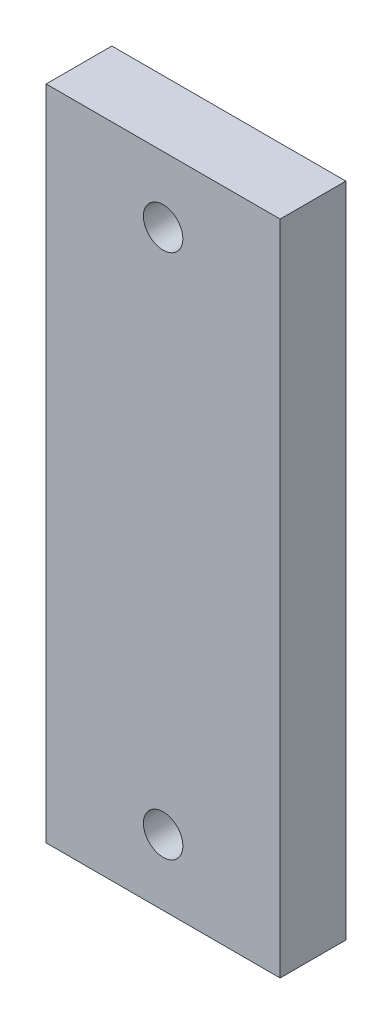
SolidWorks part; units mm, degrees
material "ABS"
ref_plane "前视基准面" through (0, 0, 0) normal (0, 0, 1) x (1, 0, 0)
ref_plane "上视基准面" through (0, 0, 0) normal (0, 1, 0) x (1, 0, 0)
ref_plane "右视基准面" through (0, 0, 0) normal (1, 0, 0) x (0, 0, -1)
sketch "草图1" plane through (0, 0, 0) normal (0, 0, 1) x (1, 0, 0)
  line L0 (0, -25) -> (0, 25) construction
  line L1 (-8.9, -25) -> (8.9, -25)
  line L2 (-8.9, -25) -> (-8.9, 25)
  line L3 (-8.9, 25) -> (8.9, 25)
  line L4 (8.9, -25) -> (8.9, 25)
  line L5 (-8.9, -25) -> (8.9, 25) construction
  line L6 (-8.9, 25) -> (8.9, -25) construction
  circle A0 centre (0, -20) radius 1.5
  circle A1 centre (0, 20) radius 1.5
  point P0 (0, 0)
  dimension "D3" = 3
  dimension "D5" = 5
  dimension "D1" = 17.8
  dimension "D2" = 50
  dimension "D4" = 5
extrude "凸台-拉伸1" add sketch "草图1" along normal blind 5
